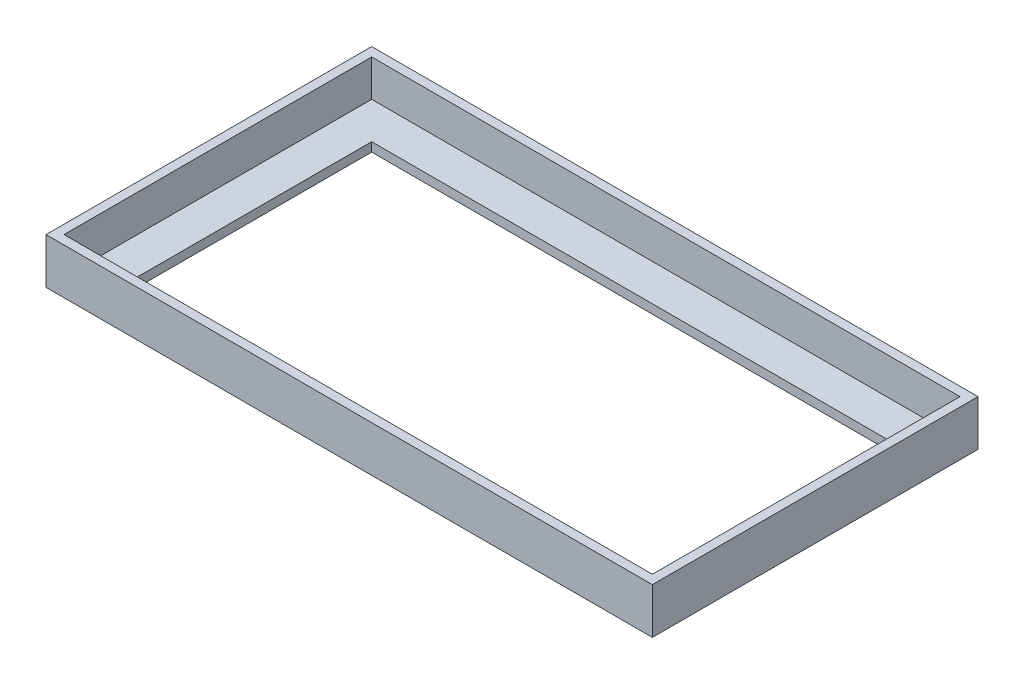
SolidWorks part; units mm, degrees
ref_plane "Front Plane" through (0, 0, 0) normal (0, 0, 1) x (1, 0, 0)
ref_plane "Top Plane" through (0, 0, 0) normal (0, 1, 0) x (1, 0, 0)
ref_plane "Right Plane" through (0, 0, 0) normal (1, 0, 0) x (0, 0, -1)
sketch "Sketch1" plane through (0, 0, 0) normal (0, 1, 0) x (1, 0, 0)
  line L1 (-168.5, 90.5) -> (168.5, 90.5)
  line L2 (-168.5, 90.5) -> (-168.5, -90.5)
  line L3 (-168.5, -90.5) -> (168.5, -90.5)
  line L4 (168.5, 90.5) -> (168.5, -90.5)
  line L5 (-168.5, 90.5) -> (168.5, -90.5) construction
  line L6 (-168.5, -90.5) -> (168.5, 90.5) construction
  point P0 (0, 0)
  dimension "D1" = 337
  dimension "D2" = 181
extrude "Boss-Extrude1" add sketch "Sketch1" along normal blind 25.4
shell "Shell1" thickness 5
sketch "Sketch2" plane through (0, 0, 0) normal (0, -1, 0) x (1, 0, 0)
  line L0 (168.5, 90.5) -> (168.5, -90.5) construction
  line L1 (-143.1, 65.1) -> (143.1, 65.1)
  line L2 (-143.1, 65.1) -> (-143.1, -65.1)
  line L3 (-143.1, -65.1) -> (143.1, -65.1)
  line L4 (143.1, 65.1) -> (143.1, -65.1)
  line L5 (-143.1, 65.1) -> (143.1, -65.1) construction
  line L6 (-143.1, -65.1) -> (143.1, 65.1) construction
  line L7 (168.5, -90.5) -> (-168.5, -90.5) construction
  point P0 (0, 0)
  dimension "D1" = 25.4
  dimension "D2" = 25.4
extrude "Cut-Extrude1" cut sketch "Sketch2" against normal through all
